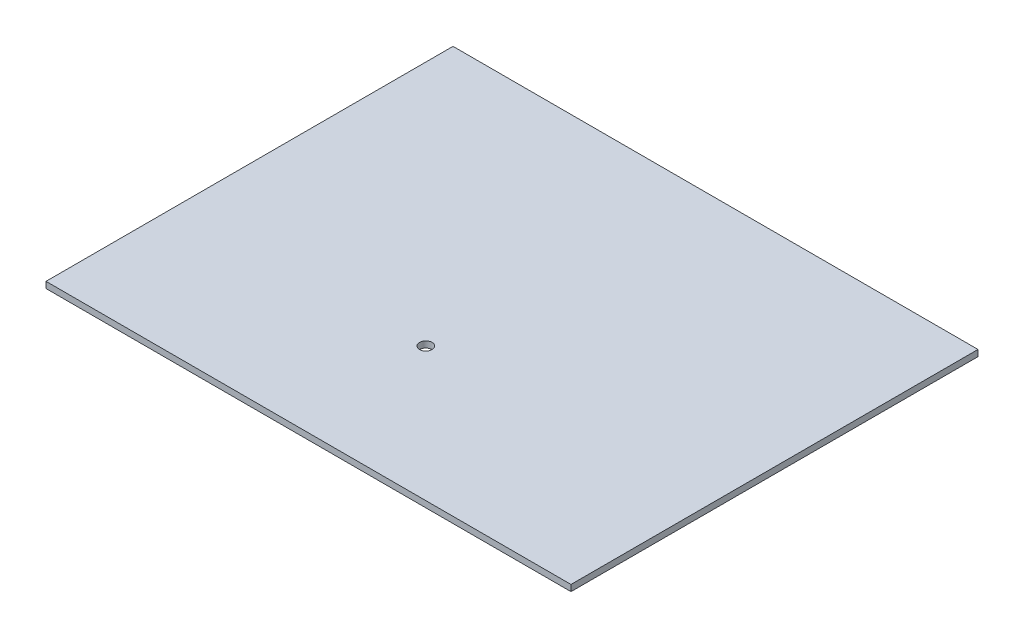
SolidWorks part; units mm, degrees
ref_plane "정면" through (0, 0, 0) normal (0, 0, 1) x (1, 0, 0)
ref_plane "윗면" through (0, 0, 0) normal (0, 1, 0) x (1, 0, 0)
ref_plane "우측면" through (0, 0, 0) normal (1, 0, 0) x (0, 0, -1)
ref_plane "평면1" through (-45, -15, 30) normal (1, 0, 0) x (0, 0, -1)
sketch "스케치3" plane through (0, -15, 0) normal (0, -1, 0) x (1, 0, 0)
  line L0 (122.68, 10) -> (122.68, -250) construction
  line L1 (-45, 30) -> (122.68, 30)
  line L2 (-45, 30) -> (-45, -100)
  line L3 (-45, -100) -> (122.68, -100)
  line L4 (122.68, 30) -> (122.68, -100)
  dimension "D1" = 130
extrude "보스-돌출1" add sketch "스케치3" along normal blind 2
sketch "스케치5" plane through (0, -17, 0) normal (0, -1, 0) x (1, 0, 0)
  circle A0 centre (33.5355, -12.7784) radius 2
extrude "컷-돌출1" cut sketch "스케치5" against normal blind 2
sketch "스케치6" plane through (0, -17, 0) normal (0, -1, 0) x (1, 0, 0)
  line L0 (-45, 30) -> (-45, -100) construction
  line L1 (-5, -49.5024) -> (5, -49.5024)
  line L2 (-5, -49.5024) -> (-5, -69.2757)
  line L3 (-5, -69.2757) -> (5, -69.2757)
  line L4 (5, -49.5024) -> (5, -69.2757)
  line L5 (20, -49.5024) -> (30, -49.5024)
  line L6 (20, -49.5024) -> (20, -69.2757)
  line L7 (20, -69.2757) -> (30, -69.2757)
  line L8 (30, -49.5024) -> (30, -69.2757)
  line L9 (45, -49.5024) -> (55, -49.5024)
  line L10 (45, -49.5024) -> (45, -69.2757)
  line L11 (45, -69.2757) -> (55, -69.2757)
  line L12 (55, -49.5024) -> (55, -69.2757)
  line L13 (70, -49.5024) -> (80, -49.5024)
  line L14 (70, -49.5024) -> (70, -69.2757)
  line L15 (70, -69.2757) -> (80, -69.2757)
  line L16 (80, -49.5024) -> (80, -69.2757)
  dimension "D1" = 10
  dimension "D2" = 10
  dimension "D3" = 10
  dimension "D4" = 10
  dimension "D5" = 40
  dimension "D6" = 15
  dimension "D7" = 15
  dimension "D8" = 15
extrude "보스-돌출2" add sketch "스케치6" along normal blind 3
